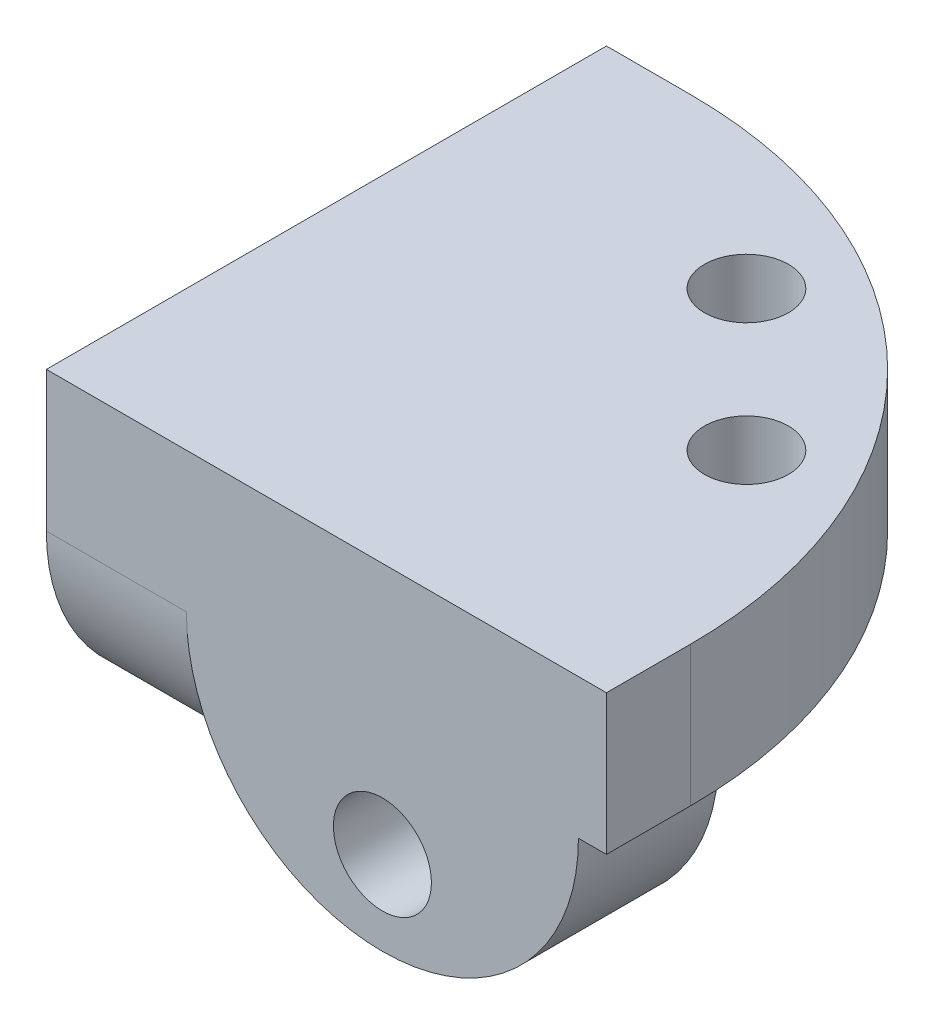
SolidWorks part; units mm, degrees
ref_plane "Front Plane" through (0, 0, 0) normal (0, 0, 1) x (1, 0, 0)
ref_plane "Top Plane" through (0, 0, 0) normal (0, 1, 0) x (1, 0, 0)
ref_plane "Right Plane" through (0, 0, 0) normal (1, 0, 0) x (0, 0, -1)
sketch "Sketch1" plane through (0, 0, 0) normal (0, 1, 0) x (1, 0, 0)
  line L0 (0, 15) -> (20, 15) construction
  line L1 (0, 0) -> (20, 0)
  line L2 (0, 0) -> (0, 20)
  line L3 (0, 20) -> (20, 20)
  line L4 (20, 0) -> (20, 20)
  line L5 (15, 20) -> (15, 0) construction
  line L6 (0, 15) -> (10, 15) construction
  line L7 (15, 0) -> (15, 10) construction
  circle A0 centre (10, 15) radius 1.5
  circle A1 centre (15, 10) radius 1.5
  dimension "D1" = 20
  dimension "D2" = 15
  dimension "D3" = 15
extrude "Boss-Extrude1" add sketch "Sketch1" along normal blind 5
sketch "Sketch2" plane through (0, 0, 0) normal (0, 0, 1) x (1, 0, 0)
  line L0 (0, 0) -> (20, 0) construction
  line L1 (19, 0) -> (5, 0)
  line L2 (12, 0) -> (12, -7) construction
  arc A0 (5, 0) -> (19, 0) centre (12, 0) ccw
  circle A1 centre (12, -4) radius 1.75
  dimension "D1" = 5
  dimension "D3" = 4
  dimension "D2" = 14
extrude "Boss-Extrude2" add sketch "Sketch2" against normal blind 5
sketch "Sketch3" plane through (0, 0, 0) normal (-1, 0, 0) x (0, 0, 1)
  line L0 (-20, 0) -> (0, 0) construction
  line L1 (0, 0) -> (-14, 0)
  line L2 (-7, 0) -> (-7, -7) construction
  arc A0 (0, 0) -> (-14, 0) centre (-7, 0) cw
  circle A1 centre (-7, -4) radius 1.75
  dimension "D1" = 0
  dimension "D3" = 4
  dimension "D4" = 3.5
  dimension "D2" = 14
extrude "Boss-Extrude3" add sketch "Sketch3" against normal blind 5
fillet "Fillet1" radius 17 1 edges at (20, 2.5, -20)
